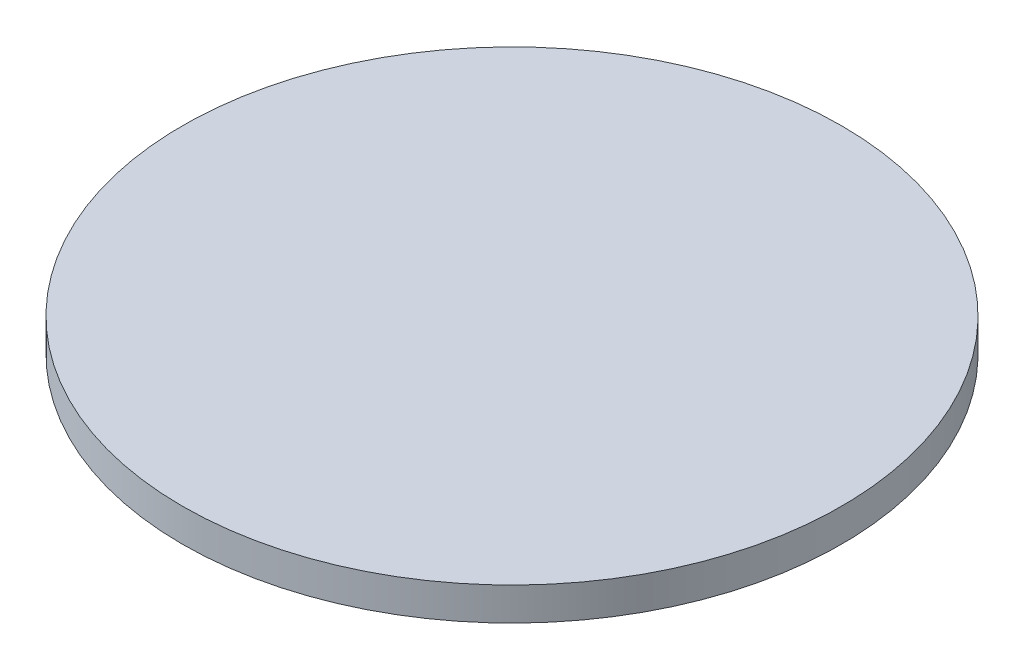
SolidWorks part; units mm, degrees
ref_plane "Front Plane" through (0, 0, 0) normal (0, 0, 1) x (1, 0, 0)
ref_plane "Top Plane" through (0, 0, 0) normal (0, 1, 0) x (1, 0, 0)
ref_plane "Right Plane" through (0, 0, 0) normal (1, 0, 0) x (0, 0, -1)
sketch "Sketch1" plane through (0, 0, 0) normal (0, 1, 0) x (1, 0, 0)
  circle A0 centre (0, 0) radius 15
  dimension "D1" = 30
extrude "Boss-Extrude1" add sketch "Sketch1" along normal blind 1.5
sketch "Sketch2" plane through (0, 0, 0) normal (0, -1, 0) x (1, 0, 0)
  circle A0 centre (0, 0) radius 10
  dimension "D1" = 20
extrude "Cut-Extrude1" cut sketch "Sketch2" against normal blind 0.5 contours A0
